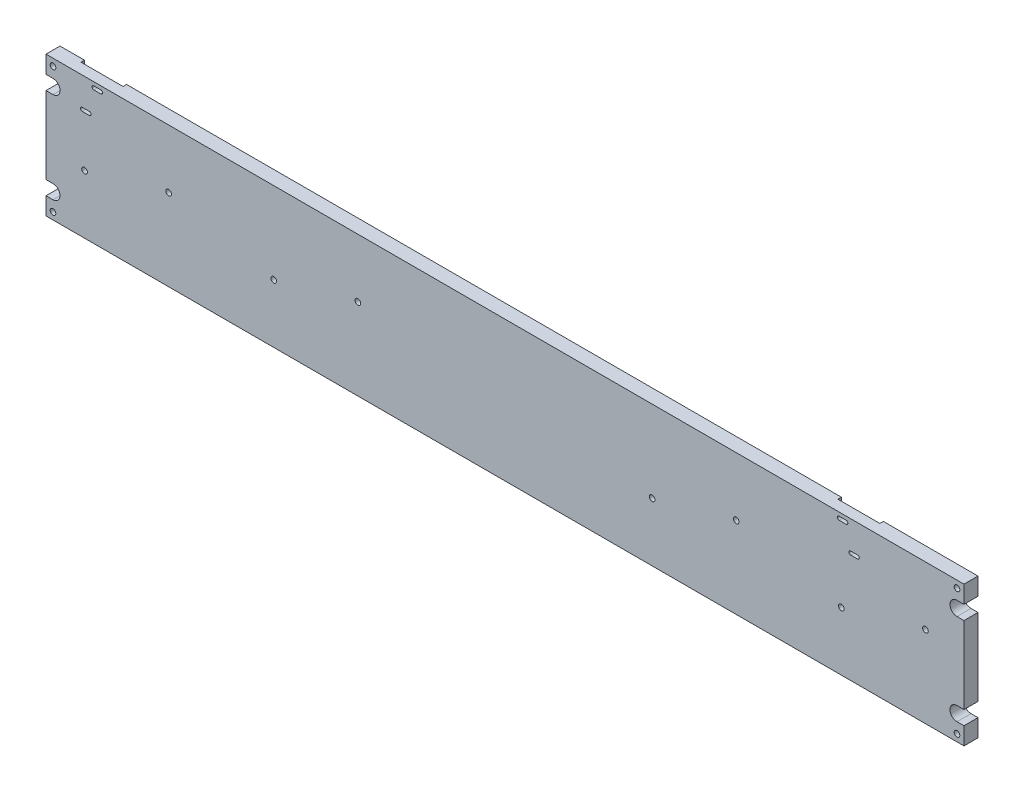
SolidWorks part; units mm, degrees
material "1060 Alloy"
ref_plane "Front Plane" through (0, 0, 0) normal (0, 0, 1) x (1, 0, 0)
ref_plane "Top Plane" through (0, 0, 0) normal (0, 1, 0) x (1, 0, 0)
ref_plane "Right Plane" through (0, 0, 0) normal (1, 0, 0) x (0, 0, -1)
sketch "Sketch1" plane through (0, 0, 0) normal (0, 0, 1) x (1, 0, 0)
  line L1 (-415.925, 63.5) -> (415.925, 63.5)
  line L2 (-415.925, 63.5) -> (-415.925, -63.5)
  line L3 (-415.925, -63.5) -> (415.925, -63.5)
  line L4 (415.925, 63.5) -> (415.925, -63.5)
  line L5 (-415.925, 63.5) -> (415.925, -63.5) construction
  line L6 (-415.925, -63.5) -> (415.925, 63.5) construction
  point P0 (0, 0)
  dimension "D1" = 831.85
  dimension "D2" = 127
extrude "Boss-Extrude1" add sketch "Sketch1" along normal mid plane 12.7
hole_wizard "#10 Clearance Hole1" positions "Sketch5" profile "Sketch4" hole size "#10" standard "ANSI Inch" end condition up to next
sketch "Sketch5" plane through (0, 0, -6.35) normal (0, 0, -1) x (-1, 0, 0)
  line L0 (-409.575, 63.5) -> (-409.575, -63.5) construction
  line L1 (-415.925, 63.5) -> (415.925, 63.5) construction
  line L2 (415.925, -63.5) -> (-415.925, -63.5) construction
  line L6 (-415.925, -63.5) -> (-415.925, 63.5) construction
  point P16 (-409.575, 57.15)
  point P20 (-409.575, -57.15)
  dimension "D1" = 6.35
  dimension "D2" = 6.35
  dimension "D3" = 6.35
sketch "Sketch4" plane through (409.575, 57.15, -6.35) normal (1, 0, 0) x (0, 1, 0)
  line L0 (0, 0) -> (0, 12.701)
  line L1 (0, 12.701) -> (2.5527, 12.701)
  line L2 (2.5527, 12.701) -> (2.5527, 0)
  line L5 (2.5527, 0) -> (0, 0)
  line L11 (0, -6.35) -> (0, 107.95) construction
  dimension "Thru Hole Dia." = 5.1054
  dimension "Thru Hole Depth" = 12.701
hole_wizard "Tapped Hole for #10-32 Helicoil1" positions "Sketch7" profile "Sketch6" tap size "#10-32" standard "Helicoil® Inch"
sketch "Sketch7" plane through (0, 0, -6.35) normal (0, 0, -1) x (-1, 0, 0)
  line L0 (-415.925, 10.3822) -> (415.925, 10.3822) construction
  line L1 (-415.925, -63.5) -> (-415.925, 63.5) construction
  line L2 (415.925, 63.5) -> (415.925, -63.5) construction
  line L4 (-415.925, -10.3822) -> (415.925, -10.3822) construction
  line L5 (0, 10.3822) -> (0, -10.3822) construction
  point P13 (-381, 10.3822)
  point P15 (-304.8, -10.3822)
  dimension "D1" = 20.7645
  dimension "D2" = 34.925
  dimension "D3" = 76.2
sketch "Sketch6" plane through (381, 10.3822, -6.35) normal (1, 0, 0) x (0, 1, 0)
  line L0 (0, 0) -> (0, 14.2328)
  line L1 (0, 14.2328) -> (2.5527, 12.699)
  line L2 (2.5527, 12.699) -> (2.5527, 0)
  line L5 (2.5527, 0) -> (0, 0)
  line L10 (0, 14.2328) -> (-2.5527, 12.699) construction
  line L11 (0, -6.35) -> (0, 107.95) construction
  dimension "Tap Drill Dia." = 5.1054
  dimension "Tap Drill Depth" = 12.699
  dimension "Drill Angle" = 118
pattern_linear "LPattern1" count 5 spacing 171.45 along (-1, 0, 0) skipping (2, 0) of "Tapped Hole for #10-32 Helicoil1"
sketch "Sketch9" plane through (0, 0, -6.35) normal (0, 0, -1) x (-1, 0, 0)
  line L0 (-422.275, 41.275) -> (-409.575, 41.275) construction
  line L1 (-415.925, -63.5) -> (-415.925, 63.5) construction
  line L2 (-422.275, 47.625) -> (-409.575, 47.625)
  line L3 (-422.275, 34.925) -> (-409.575, 34.925)
  line L4 (-415.925, 63.5) -> (415.925, 63.5) construction
  line L5 (-415.925, 0) -> (-378.8662, 0) construction
  line L6 (-422.275, -41.275) -> (-409.575, -41.275) construction
  line L7 (-422.275, -47.625) -> (-409.575, -47.625)
  line L8 (-422.275, -34.925) -> (-409.575, -34.925)
  arc A0 (-422.275, 47.625) -> (-422.275, 34.925) centre (-422.275, 41.275) ccw
  arc A1 (-409.575, 34.925) -> (-409.575, 47.625) centre (-409.575, 41.275) ccw
  arc A2 (-422.275, -47.625) -> (-422.275, -34.925) centre (-422.275, -41.275) cw
  arc A3 (-409.575, -34.925) -> (-409.575, -47.625) centre (-409.575, -41.275) cw
  point P4 (-415.925, 41.275)
  point P16 (-415.925, -41.275)
  dimension "D2" = 6.35
  dimension "D1" = 22.225
  dimension "D3" = 6.35
extrude "Cut-Extrude1" cut sketch "Sketch9" against normal through all
mirror "Mirror1" about plane through (0, 0, 0) normal (1, 0, 0) of "Cut-Extrude1", "#10 Clearance Hole1"
hole_wizard "#4 Clearance Hole1" [suppressed] positions "Sketch11" profile "Sketch10" hole size "#4" standard "ANSI Inch"
sketch "Sketch11" plane through (0, 0, -6.35) normal (0, 0, -1) x (-1, 0, 0)
  line L0 (379.857, 36.576) -> (369.443, 58.674) construction
  line L2 (374.65, 47.625) -> (415.925, 47.625) construction
  line L3 (415.925, 34.925) -> (415.925, -34.925) construction
  line L4 (-415.925, 63.5) -> (415.925, 63.5) construction
  line L5 (-415.925, 47.625) -> (-311.15, 47.625) construction
  line L6 (-415.925, -34.925) -> (-415.925, 34.925) construction
  line L8 (-316.357, 36.576) -> (-305.943, 58.674) construction
  point P0 (379.857, 36.576)
  point P1 (369.443, 58.674)
  point P26 (-316.357, 36.576)
  point P27 (-305.943, 58.674)
  dimension "D1" = 10.414
  dimension "D2" = 22.098
  dimension "D3" = 41.275
  dimension "D4" = 15.875
  dimension "D5" = 22.098
  dimension "D6" = 10.414
  dimension "D7" = 104.775
sketch "Sketch10" plane through (-379.857, 36.576, -6.35) normal (1, 0, 0) x (0, 1, 0)
  line L0 (0, 0) -> (0, 12.7)
  line L1 (0, 12.7) -> (1.6319, 12.7)
  line L2 (1.6319, 12.7) -> (1.6319, 0)
  line L5 (1.6319, 0) -> (0, 0)
  line L11 (0, -6.35) -> (0, 107.95) construction
  dimension "Thru Hole Dia." = 3.2639
  dimension "Thru Hole Depth" = 12.7
chamfer "Chamfer1" [suppressed] distance 0.508 angle 45
chamfer "Chamfer2" [suppressed] distance 0.508 angle 45
sketch "Sketch12" [suppressed] plane through (0, 0, -6.35) normal (0, 0, -1) x (-1, 0, 0)
  line L0 (-415.925, 63.5) -> (415.925, 63.5) construction
  line L1 (-330.2, 63.5) -> (-292.1, 63.5)
  line L2 (-330.2, 63.5) -> (-330.2, 31.75)
  line L3 (-323.85, 25.4) -> (-298.45, 25.4)
  line L4 (-292.1, 63.5) -> (-292.1, 31.75)
  line L5 (-305.943, 58.674) -> (-316.357, 36.576) construction
  line L6 (-311.15, 47.625) -> (-311.15, 63.5) construction
  line L7 (369.443, 58.674) -> (379.857, 36.576) construction
  line L8 (355.6, 63.5) -> (393.7, 63.5)
  line L9 (355.6, 63.5) -> (355.6, 31.75)
  line L10 (361.95, 25.4) -> (387.35, 25.4)
  line L11 (393.7, 63.5) -> (393.7, 31.75)
  line L12 (374.65, 47.625) -> (374.65, 63.5) construction
  arc A0 (-298.45, 25.4) -> (-292.1, 31.75) centre (-298.45, 31.75) ccw
  arc A1 (-330.2, 31.75) -> (-323.85, 25.4) centre (-323.85, 31.75) ccw
  arc A2 (387.35, 25.4) -> (393.7, 31.75) centre (387.35, 31.75) ccw
  arc A3 (355.6, 31.75) -> (361.95, 25.4) centre (361.95, 31.75) ccw
  point P16 (-330.2, 25.4)
  dimension "D3" = 6.35
  dimension "D4" = 6.35
  dimension "D1" = 38.1
  dimension "D2" = 38.1
extrude "Cut-Extrude2" [suppressed] cut sketch "Sketch12" against normal blind 3.175
sketch "Sketch13" plane through (0, 0, 6.35) normal (0, 0, 1) x (1, 0, 0)
  line L0 (-415.925, 47.625) -> (-374.65, 47.625) construction
  line L1 (-379.857, 36.576) -> (-369.443, 58.674) construction
  line L2 (-372.618, 58.674) -> (-366.268, 58.674) construction
  line L3 (-372.618, 60.2615) -> (-366.268, 60.2615)
  line L4 (-372.618, 57.0865) -> (-366.268, 57.0865)
  line L5 (-383.032, 36.576) -> (-376.682, 36.576) construction
  line L6 (-383.032, 38.1635) -> (-376.682, 38.1635)
  line L7 (-383.032, 34.9885) -> (-376.682, 34.9885)
  line L8 (415.925, 47.625) -> (311.15, 47.625) construction
  line L9 (316.357, 36.576) -> (305.943, 58.674) construction
  line L10 (302.768, 58.674) -> (309.118, 58.674) construction
  line L11 (302.768, 60.2615) -> (309.118, 60.2615)
  line L12 (302.768, 57.0865) -> (309.118, 57.0865)
  line L13 (313.182, 36.576) -> (319.532, 36.576) construction
  line L14 (313.182, 38.1635) -> (319.532, 38.1635)
  line L15 (313.182, 34.9885) -> (319.532, 34.9885)
  arc A0 (-372.618, 60.2615) -> (-372.618, 57.0865) centre (-372.618, 58.674) ccw
  arc A1 (-366.268, 57.0865) -> (-366.268, 60.2615) centre (-366.268, 58.674) ccw
  arc A2 (-383.032, 38.1635) -> (-383.032, 34.9885) centre (-383.032, 36.576) ccw
  arc A3 (-376.682, 34.9885) -> (-376.682, 38.1635) centre (-376.682, 36.576) ccw
  arc A4 (302.768, 60.2615) -> (302.768, 57.0865) centre (302.768, 58.674) ccw
  arc A5 (309.118, 57.0865) -> (309.118, 60.2615) centre (309.118, 58.674) ccw
  arc A6 (313.182, 38.1635) -> (313.182, 34.9885) centre (313.182, 36.576) ccw
  arc A7 (319.532, 34.9885) -> (319.532, 38.1635) centre (319.532, 36.576) ccw
  point P7 (-369.443, 58.674)
  point P13 (-379.857, 36.576)
  point P26 (305.943, 58.674)
  point P32 (316.357, 36.576)
  dimension "D5" = 1.5875
  dimension "D1" = 41.275
  dimension "D2" = 10.414
  dimension "D3" = 22.098
  dimension "D4" = 6.35
  dimension "D6" = 104.775
  dimension "D7" = 10.414
  dimension "D8" = 22.098
extrude "Cut-Extrude3" cut sketch "Sketch13" against normal up to next
sketch "Sketch14" plane through (0, 0, -6.35) normal (0, 0, -1) x (-1, 0, 0)
  line L0 (-415.925, 63.5) -> (415.925, 63.5) construction
  line L1 (-330.2, 63.5) -> (-292.1, 63.5)
  line L2 (-330.2, 63.5) -> (-330.2, 31.75)
  line L3 (-323.85, 25.4) -> (-298.45, 25.4)
  line L4 (-292.1, 63.5) -> (-292.1, 31.75)
  line L6 (355.6, 63.5) -> (393.7, 63.5)
  line L7 (355.6, 63.5) -> (355.6, 31.75)
  line L8 (361.95, 25.4) -> (387.35, 25.4)
  line L9 (393.7, 63.5) -> (393.7, 31.75)
  line L10 (-330.2, 25.4) -> (-292.1, 63.5) construction
  line L11 (355.6, 25.4) -> (393.7, 63.5) construction
  line L12 (-415.925, -34.925) -> (-415.925, 34.925) construction
  line L13 (415.925, 63.5) -> (415.925, 47.625) construction
  arc A0 (387.35, 25.4) -> (393.7, 31.75) centre (387.35, 31.75) ccw
  arc A1 (355.6, 31.75) -> (361.95, 25.4) centre (361.95, 31.75) ccw
  arc A2 (-298.45, 25.4) -> (-292.1, 31.75) centre (-298.45, 31.75) ccw
  arc A3 (-330.2, 31.75) -> (-323.85, 25.4) centre (-323.85, 31.75) ccw
  point P10 (-311.15, 44.45)
  point P11 (374.65, 44.45)
  dimension "D4" = 6.35
  dimension "D1" = 38.1
  dimension "D2" = 104.775
  dimension "D3" = 41.275
  dimension "D5" = 38.1
extrude "Cut-Extrude4" cut sketch "Sketch14" against normal blind 3.175
